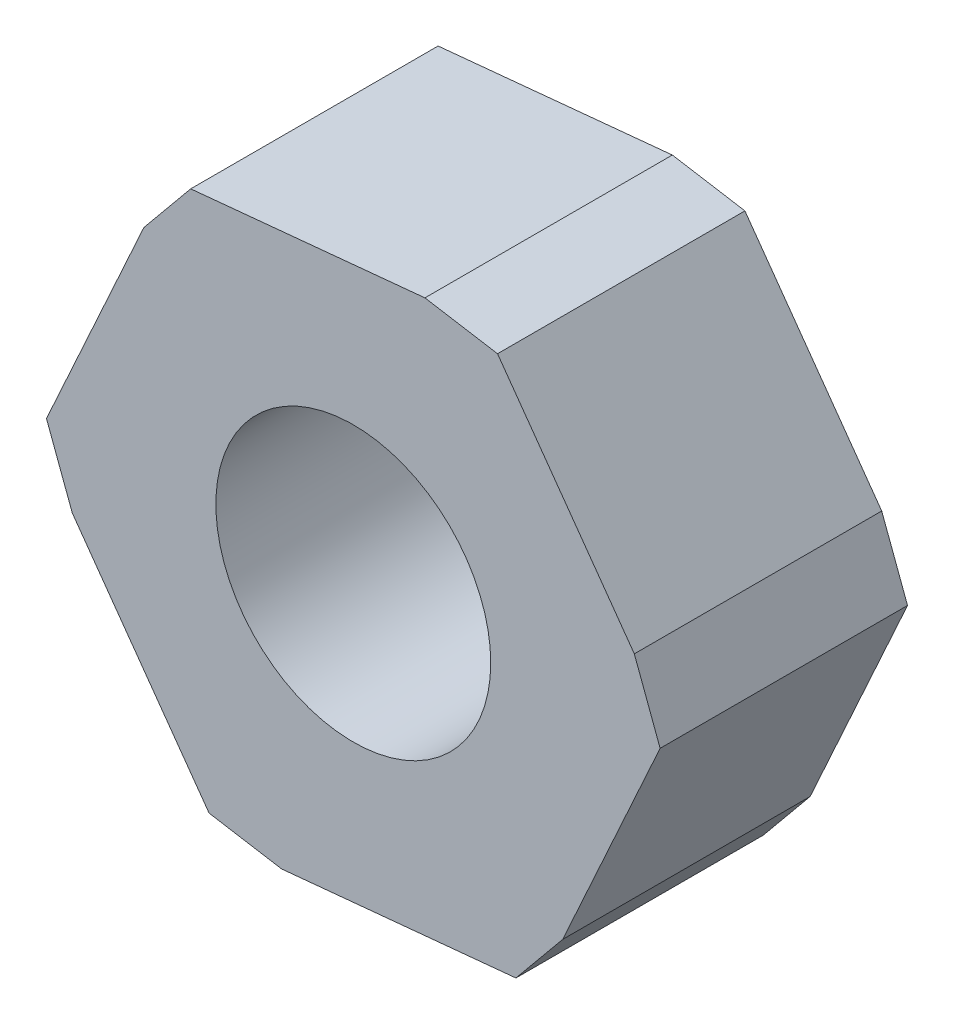
SolidWorks part; units mm, degrees
ref_plane "Plano frontal" through (0, 0, 0) normal (0, 0, 1) x (1, 0, 0)
ref_plane "Plano superior" through (0, 0, 0) normal (0, 1, 0) x (1, 0, 0)
ref_plane "Plano direito" through (0, 0, 0) normal (1, 0, 0) x (0, 0, -1)
sketch "Esboço1" plane through (0, 0, 0) normal (0, 0, 1) x (1, 0, 0)
  line L2 (-5.1444, -2.8725) -> (-2.7536, 2.3827)
  line L3 (-2.7536, 2.3827) -> (-6.1094, 7.0808)
  line L4 (-6.1094, 7.0808) -> (-11.856, 6.5236)
  line L5 (-11.856, 6.5236) -> (-14.2467, 1.2684)
  line L6 (-14.2467, 1.2684) -> (-10.891, -3.4297)
  line L7 (-10.891, -3.4297) -> (-5.1444, -2.8725)
  circle A0 centre (-8.5002, 1.8255) radius 5 construction
  dimension "D1" = 10
extrude "Ressalto-extrusão1" add sketch "Esboço1" along normal blind 4.5
sketch "Esboço2" plane through (0, 0, 4.5) normal (0, 0, 1) x (1, 0, 0)
  line L0 (-8.9827, 6.8022) -> (-8.0177, -3.1511) construction
  line L1 (-6.1094, 7.0808) -> (-11.856, 6.5236) construction
  line L2 (-10.891, -3.4297) -> (-5.1444, -2.8725) construction
  line L3 (-14.2467, 1.2684) -> (-2.7536, 2.3827) construction
  circle A0 centre (-8.5002, 1.8255) radius 2.5
  dimension "D1" = 5
extrude "Corte-extrusão1" cut sketch "Esboço2" against normal blind 7.5
chamfer "Chanfro1" distance 0.4 angle 45 6 edges at (-2.7536, 2.3827, 2.25) (-6.1094, 7.0808, 2.25) (-5.1444, -2.8725, 2.25) (-10.891, -3.4297, 2.25) (-14.2467, 1.2684, 2.25) (-11.856, 6.5236, 2.25)
